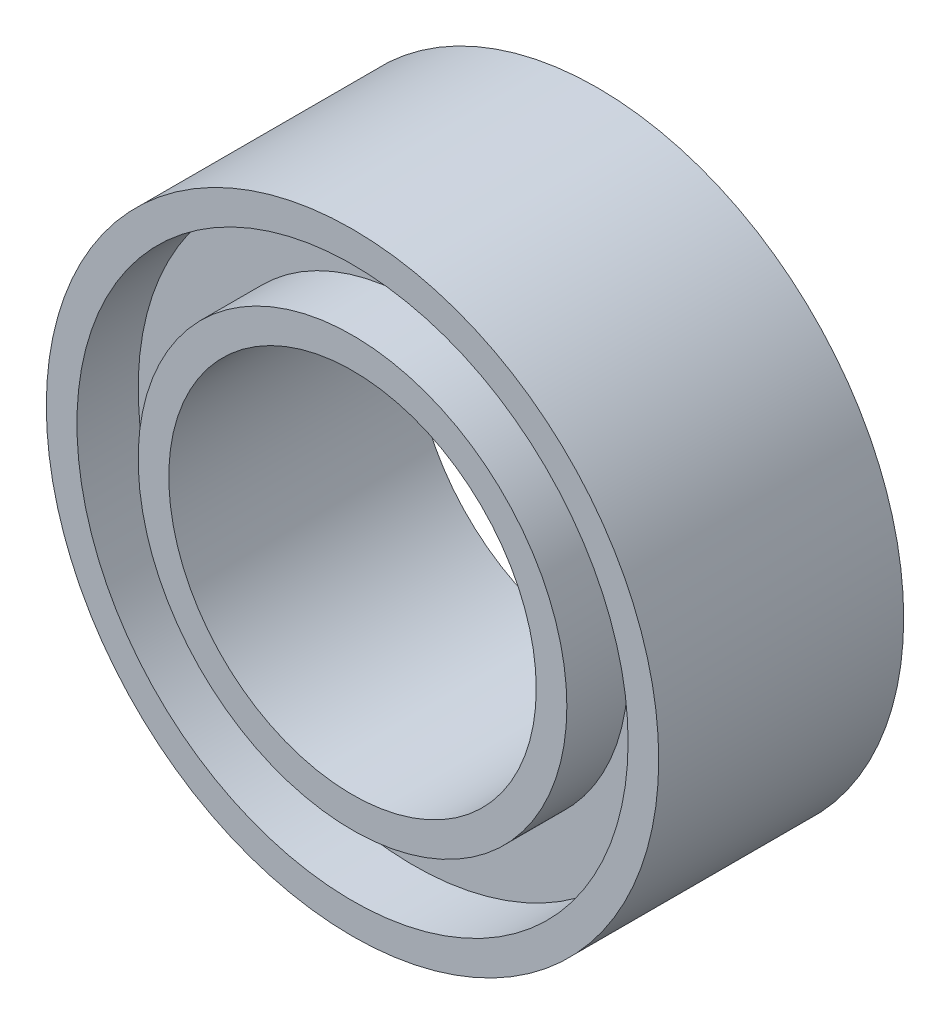
SolidWorks part; units mm, degrees
ref_plane "前视基准面" through (0, 0, 0) normal (0, 0, 1) x (1, 0, 0)
ref_plane "上视基准面" through (0, 0, 0) normal (0, 1, 0) x (1, 0, 0)
ref_plane "右视基准面" through (0, 0, 0) normal (1, 0, 0) x (0, 0, -1)
sketch "草图1" plane through (0, 0, 0) normal (0, 0, 1) x (1, 0, 0)
  circle A0 centre (0, 0) radius 5
  circle A1 centre (0, 0) radius 3
  dimension "D1" = 10
  dimension "D2" = 6
extrude "凸台-拉伸1" add sketch "草图1" along normal blind 4
sketch "草图2" plane through (0, 0, 4) normal (0, 0, 1) x (1, 0, 0)
  circle A0 centre (0, 0) radius 3.5
  circle A1 centre (0, 0) radius 4.5
  dimension "D1" = 7
  dimension "D2" = 9
extrude "切除-拉伸1" cut sketch "草图2" against normal blind 1
sketch "草图3" plane through (0, 0, 0) normal (0, 0, -1) x (-1, 0, 0)
  circle A0 centre (0, 0) radius 3.5
  circle A1 centre (0, 0) radius 4.5
  dimension "D1" = 7
  dimension "D2" = 9
extrude "切除-拉伸2" cut sketch "草图3" against normal blind 1
